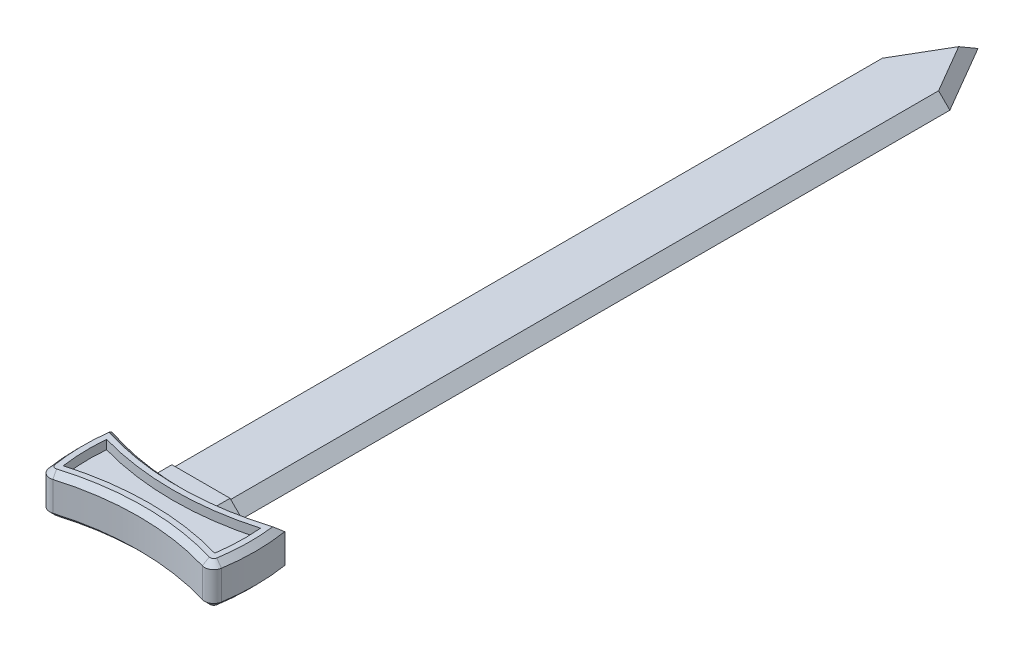
SolidWorks part; units mm, degrees
ref_plane "前视基准面" through (0, 0, 0) normal (0, 0, 1) x (1, 0, 0)
ref_plane "上视基准面" through (0, 0, 0) normal (0, 1, 0) x (1, 0, 0)
ref_plane "右视基准面" through (0, 0, 0) normal (1, 0, 0) x (0, 0, -1)
sketch "草图1" plane through (0, 0, 0) normal (0, 1, 0) x (1, 0, 0)
  line L0 (0, 0) -> (0, 690) construction
  line L1 (0, 690) -> (0, 630) construction
  line L2 (-35, 0) -> (35, 0)
  line L3 (-35, 0) -> (-35, 630)
  line L4 (-35, 630) -> (0, 690)
  line L5 (35, 630) -> (0, 690)
  line L6 (35, 0) -> (35, 630)
  dimension "D1" = 690
  dimension "D2" = 60
  dimension "D3" = 70
ref_plane "基准面1" through (0, 10, 0) normal (0, 1, 0) x (1, 0, 0)
sketch "草图4" plane through (0, 10, 0) normal (0, 1, 0) x (1, 0, 0)
  line L0 (25, 0) -> (-25, 0)
  line L1 (-25, 0) -> (-25, 630)
  line L2 (-25, 630) -> (0, 672.8571)
  line L3 (0, 0) -> (0, 690) construction
  line L4 (-35, 630) -> (0, 690) construction
  line L5 (0, -55) -> (0, 55) construction
  line L6 (25, 630) -> (0, 672.8571)
  line L7 (25, 0) -> (25, 630)
  point P2 (0, 0)
  dimension "D1" = 50
loft "放样1" add profiles "草图4", "草图1"
mirror "镜向1" about plane through (0, 0, 0) normal (0, 1, 0) of "放样1"
sketch "草图5" plane through (0, 0, 0) normal (0, 1, 0) x (1, 0, 0)
  line L0 (0, -30.5) -> (0, -55.5) construction
  line L1 (0, -55.5) -> (0, -30.5) construction
  line L2 (-79, -30.5) -> (79, -30.5) construction
  line L3 (0, -30.5) -> (0, 0) construction
  arc A0 (-66.3468, -65.1892) -> (66.3468, -65.1892) centre (0, -287.5) cw
  arc A1 (76.7912, -2.3877) -> (76.7912, -58.6123) centre (-101, -30.5) cw
  arc A2 (-76.7912, -2.3877) -> (-76.7912, -58.6123) centre (101, -30.5) ccw
  arc A4 (66.3468, -65.1892) -> (76.7912, -58.6123) centre (68.6918, -57.3316) ccw
  arc A5 (-66.3468, -65.1892) -> (-76.7912, -58.6123) centre (-68.6918, -57.3316) cw
  arc A6 (-76.7912, -2.3877) -> (76.7912, -2.3877) centre (0, 224.9955) ccw
  point P10 (0, -55.5)
  point P15 (79, -30.5)
  dimension "D4" = 232
  dimension "D5" = 180
  dimension "D6" = 8.2
  dimension "D7" = 240
  dimension "D1" = 25
  dimension "D2" = 158
  dimension "D3" = 30.5
extrude "凸台-拉伸1" add sketch "草图5" along normal mid plane 36 separate body
chamfer "倒角1" distance 5 angle 45 11 edges at (79, -18, 30.5) (73.0612, -18, 64.2705) (0, -18, 55.5) (-73.0612, -18, 64.2705) (-79, -18, 30.5) (79, 18, 30.5) (73.0612, 18, 64.2705) (0, 18, 55.5) (-73.0612, 18, 64.2705) (-79, 18, 30.5) (0, 18, 15.0045)
chamfer "倒角2" distance 5 angle 45 1 edges at (0, -18, 15.0045)
sketch "草图6" plane through (0, 18, 0) normal (0, 1, 0) x (1, 0, 0)
  arc A12 (67.2218, -55.0237) -> (68.3355, -15.4837) centre (-101, -30.5) ccw
  arc A13 (-68.3355, -15.4837) -> (68.3355, -15.4837) centre (0, 224.9955) ccw
  arc A14 (-68.3355, -15.4837) -> (-67.2218, -55.0237) centre (101, -30.5) ccw
  arc A15 (67.2218, -55.0237) -> (-67.2218, -55.0237) centre (0, -287.5) ccw
  arc A16 (67.2218, -55.0237) -> (68.3355, -15.4837) centre (-101, -30.5) ccw
  arc A17 (-68.3355, -15.4837) -> (68.3355, -15.4837) centre (0, 224.9955) ccw
  arc A18 (-68.3355, -15.4837) -> (-67.2218, -55.0237) centre (101, -30.5) ccw
  arc A19 (67.2218, -55.0237) -> (-67.2218, -55.0237) centre (0, -287.5) ccw
  dimension "D1" = 5
extrude "切除-拉伸1" cut sketch "草图6" against normal blind 8
mirror "镜向2" about plane through (0, 0, 0) normal (0, 1, 0) of "切除-拉伸1"
sketch "草图7" plane through (0, 0, 0) normal (0, 0, 1) x (1, 0, 0)
  line L12 (-25.8284, 12) -> (-37.8284, 0)
  line L13 (-37.8284, 0) -> (-25.8284, -12)
  line L14 (-25.8284, -12) -> (25.8284, -12)
  line L15 (25.8284, -12) -> (37.8284, 0)
  line L16 (37.8284, 0) -> (25.8284, 12)
  line L17 (25.8284, 12) -> (-25.8284, 12)
  line L18 (-25.8284, 12) -> (-37.8284, 0)
  line L19 (-37.8284, 0) -> (-25.8284, -12)
  line L20 (-25.8284, -12) -> (25.8284, -12)
  line L21 (25.8284, -12) -> (37.8284, 0)
  line L22 (37.8284, 0) -> (25.8284, 12)
  line L23 (25.8284, 12) -> (-25.8284, 12)
  dimension "D1" = 2
extrude "凸台-拉伸2" add sketch "草图7" along normal up to surface (12.0045 mm away)
